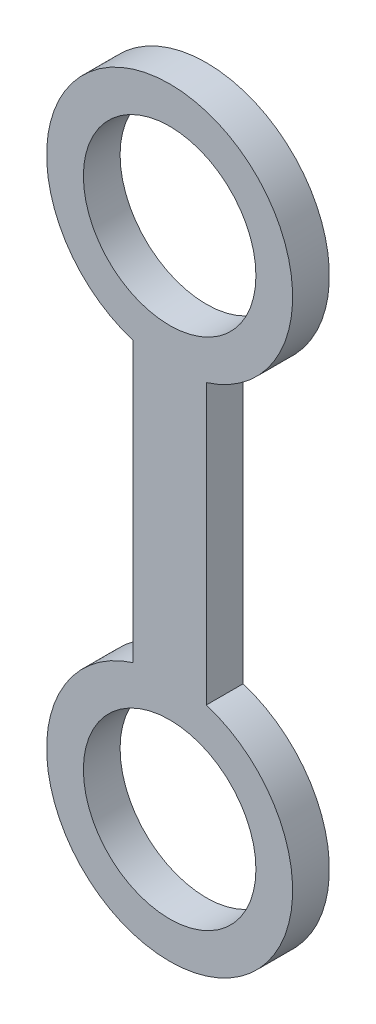
SolidWorks part; units mm, degrees
ref_plane "Plan de face" through (0, 0, 0) normal (0, 0, 1) x (1, 0, 0)
ref_plane "Plan de dessus" through (0, 0, 0) normal (0, 1, 0) x (1, 0, 0)
ref_plane "Plan de droite" through (0, 0, 0) normal (1, 0, 0) x (0, 0, -1)
sketch "Esquisse1" plane through (0, 0, 0) normal (0, 0, 1) x (1, 0, 0)
  line L0 (0, 140) -> (0, 0) construction
  line L1 (-10, 108.0274) -> (-10, 31.9726)
  line L2 (0, 140) -> (0, 165) construction
  line L3 (0, 0) -> (0, -25) construction
  line L4 (10, 108.0274) -> (10, 31.9726)
  circle A0 centre (0, 0) radius 23.5
  circle A1 centre (0, 140) radius 23.5
  arc A2 (-10, 108.0274) -> (10, 108.0274) centre (0, 140) cw
  arc A3 (-10, 31.9726) -> (10, 31.9726) centre (0, 0) ccw
  dimension "D2" = 47
  dimension "D3" = 47
  dimension "D4" = 10
  dimension "D5" = 10
  dimension "D1" = 140
  dimension "D6" = 10
extrude "Boss.-Extru.1" add sketch "Esquisse1" along normal blind 10
